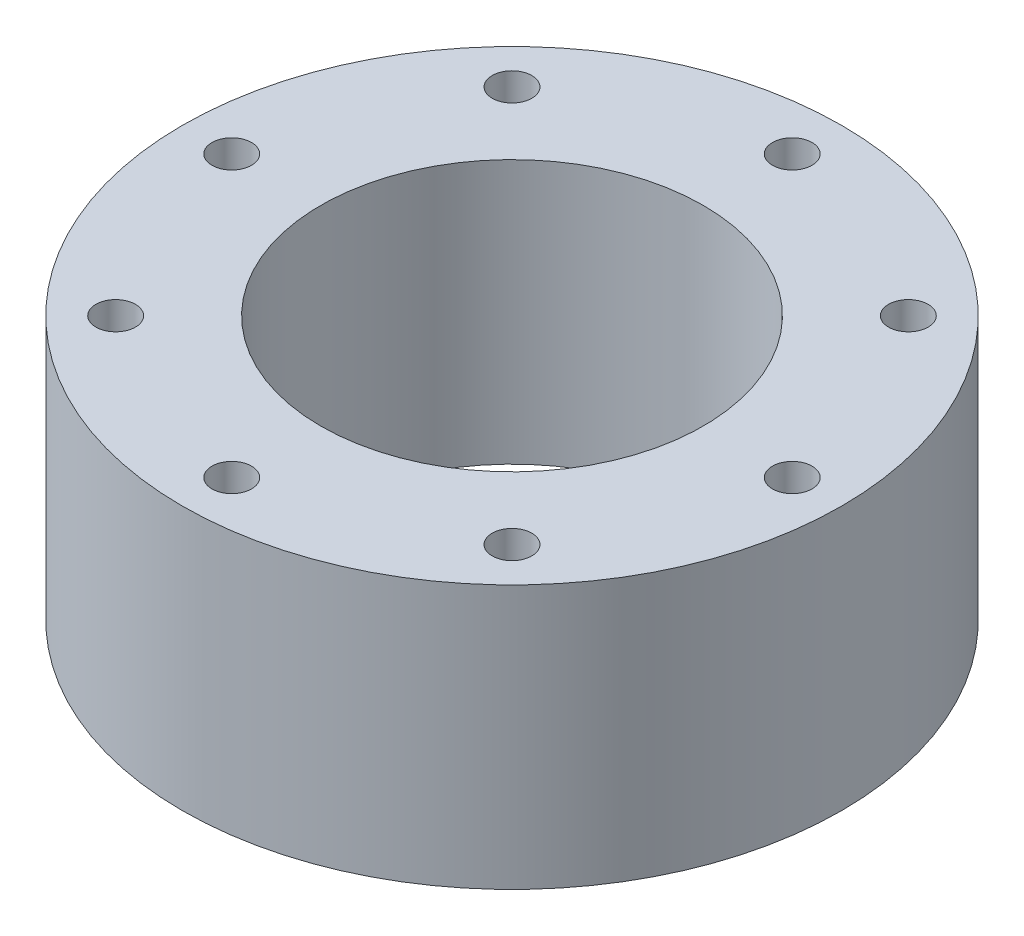
SolidWorks part; units mm, degrees
ref_plane "Front Plane" through (0, 0, 0) normal (0, 0, 1) x (1, 0, 0)
ref_plane "Top Plane" through (0, 0, 0) normal (0, 1, 0) x (1, 0, 0)
ref_plane "Right Plane" through (0, 0, 0) normal (1, 0, 0) x (0, 0, -1)
sketch "Sketch1" plane through (0, 0, 0) normal (0, 1, 0) x (1, 0, 0)
  line L0 (0, 0) -> (-15.026, 15.026) construction
  line L1 (0, 33.6337) -> (0, -34.7858) construction
  line L2 (-12.6586, 0) -> (11.6906, 0) construction
  circle A0 centre (0, 0) radius 25
  circle A1 centre (0, -21.25) radius 1.5
  circle A2 centre (-15.026, -15.026) radius 1.5
  circle A3 centre (-21.25, 0) radius 1.5
  circle A4 centre (-15.026, 15.026) radius 1.5
  circle A5 centre (0, 21.25) radius 1.5
  circle A6 centre (15.026, 15.026) radius 1.5
  circle A7 centre (21.25, 0) radius 1.5
  circle A8 centre (15.026, -15.026) radius 1.5
  circle A9 centre (0, 0) radius 21.25 construction
  circle A10 centre (0, 0) radius 14.5
  point P22 (0, 0)
  point P23 (0, 0)
  point P26 (0, 0)
  point P27 (0, 0)
  dimension "D1" = 50
  dimension "D2" = 3
  dimension "D3" = 42.5
  dimension "D4" = 29
  dimension "D5" = 45
extrude "Boss-Extrude1" add sketch "Sketch1" along normal mid plane 20
